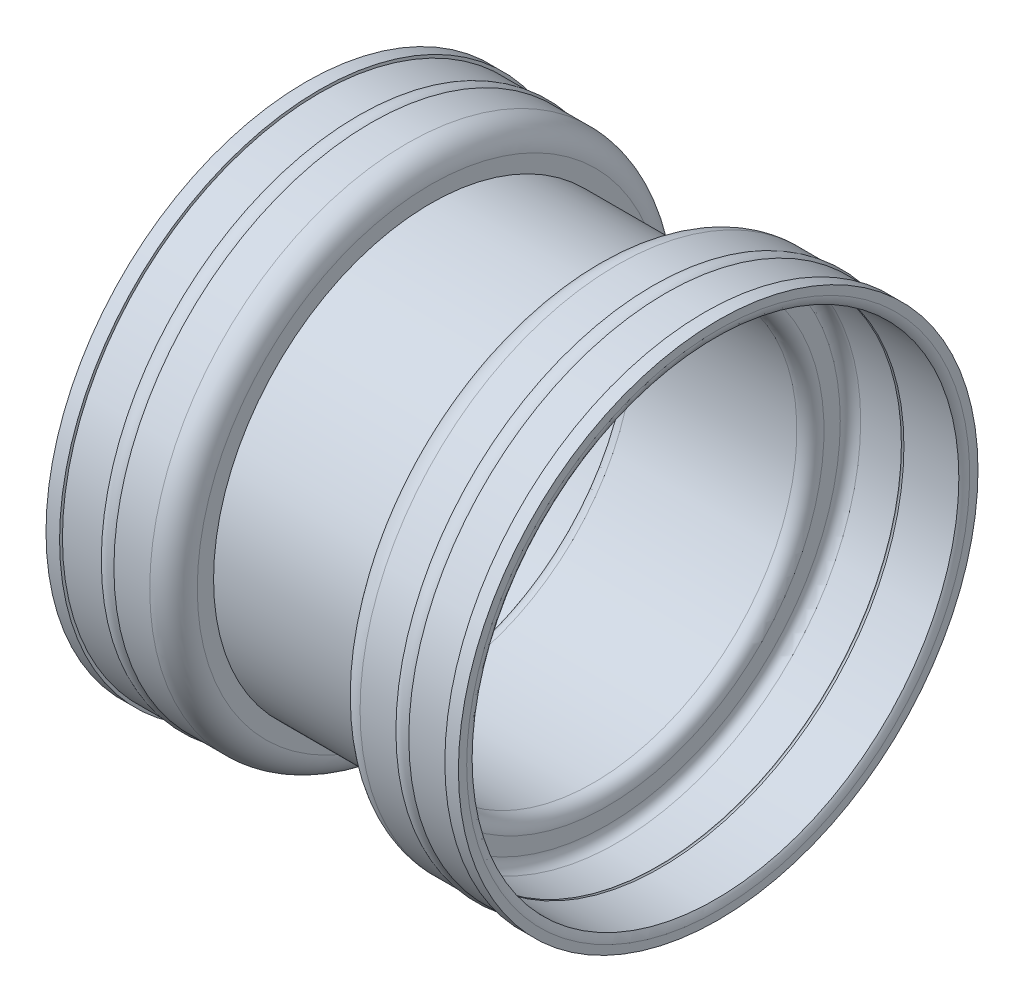
SolidWorks part; units mm, degrees
ref_plane "Płaszczyzna przednia" through (0, 0, 0) normal (0, 0, 1) x (1, 0, 0)
ref_plane "Płaszczyzna górna" through (0, 0, 0) normal (0, 1, 0) x (1, 0, 0)
ref_plane "Płaszczyzna prawa" through (0, 0, 0) normal (1, 0, 0) x (0, 0, -1)
sketch "Szkic1" plane through (0, 0, 0) normal (0, 0, 1) x (1, 0, 0)
  line L0 (0, 0) -> (0, 150) construction
  line L1 (0, 150) -> (-60, 150)
  line L2 (-70, 160) -> (-70, 172)
  line L3 (-77.5202, 179.5202) -> (-107.5202, 179.5202)
  line L4 (-152, 185.4055) -> (-152, 191.5202)
  line L5 (60, 150) -> (-60, 150) construction
  line L6 (-109.5136, 179.4055) -> (-150, 179.4055)
  line L7 (-160, 148.1328) -> (-160, 234.9075) construction
  line L8 (0, 0) -> (339.9072, 0) construction
  arc A0 (-60, 150) -> (-70, 160) centre (-60, 160) cw
  arc A1 (-70, 172) -> (-77.5202, 179.5202) centre (-77.5202, 172) ccw
  arc A2 (-150, 179.4055) -> (-152, 185.4055) centre (-142, 185.4055) cw
  arc A3 (-152, 191.5202) -> (-160, 199.5202) centre (-160, 191.5202) ccw construction
  arc A4 (-107.5202, 179.5202) -> (-109.5136, 179.4055) centre (-108.5202, 179.5202) ccw
  point P18 (0, 150)
  point P24 (-160, 191.5202)
  point P26 (0, 0)
  dimension "D2" = 10
  dimension "D4" = 120
  dimension "D5" = 8
  dimension "D6" = 22
  dimension "D9" = 6.1147
  dimension "D10" = 1
  dimension "D12" = 10
  dimension "D13" = 160
  dimension "D1" = 150
  dimension "D3" = 120
  dimension "D7" = 6
  dimension "D8" = 12
  dimension "D11" = 30
revolve "Obrót-cienka ścianka1" add sketch "Szkic1" angle 360 about L8
mirror "Lustro4" about plane through (0, 160, 0) normal (1, 0, 0) of bodies 101
sketch "Szkic3" plane through (0, 0, 0) normal (1, 0, 0) x (0, 0, -1)
  circle A0 centre (0, 0) radius 172
  circle A1 centre (0, 0) radius 160
  circle A2 centre (0, 0) radius 108.7382
  circle A3 centre (0, 0) radius 191.5202
  point P6 (0, 0)
